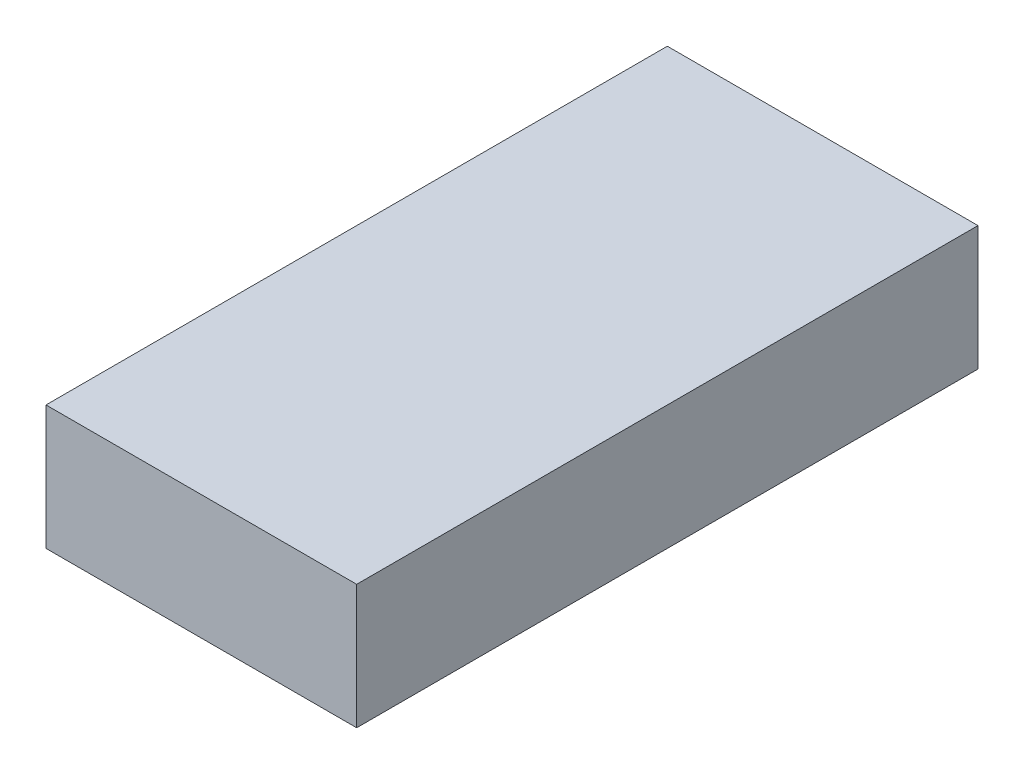
SolidWorks part; units mm, degrees
ref_plane "Přední rovina" through (0, 0, 0) normal (0, 0, 1) x (1, 0, 0)
ref_plane "Horní rovina" through (0, 0, 0) normal (0, 1, 0) x (1, 0, 0)
ref_plane "Pravá rovina" through (0, 0, 0) normal (1, 0, 0) x (0, 0, -1)
sketch "Skica1" plane through (0, 0, 0) normal (0, 0, 1) x (1, 0, 0)
  line L7 (0, 0) -> (-50, 0)
  line L8 (0, 0) -> (0, 20)
  line L9 (0, 20) -> (-50, 20)
  line L10 (-50, 0) -> (-50, 20)
  dimension "D1" = 50
  dimension "D2" = 20
extrude "Přidat vysunutím1" add sketch "Skica1" along normal blind 100
